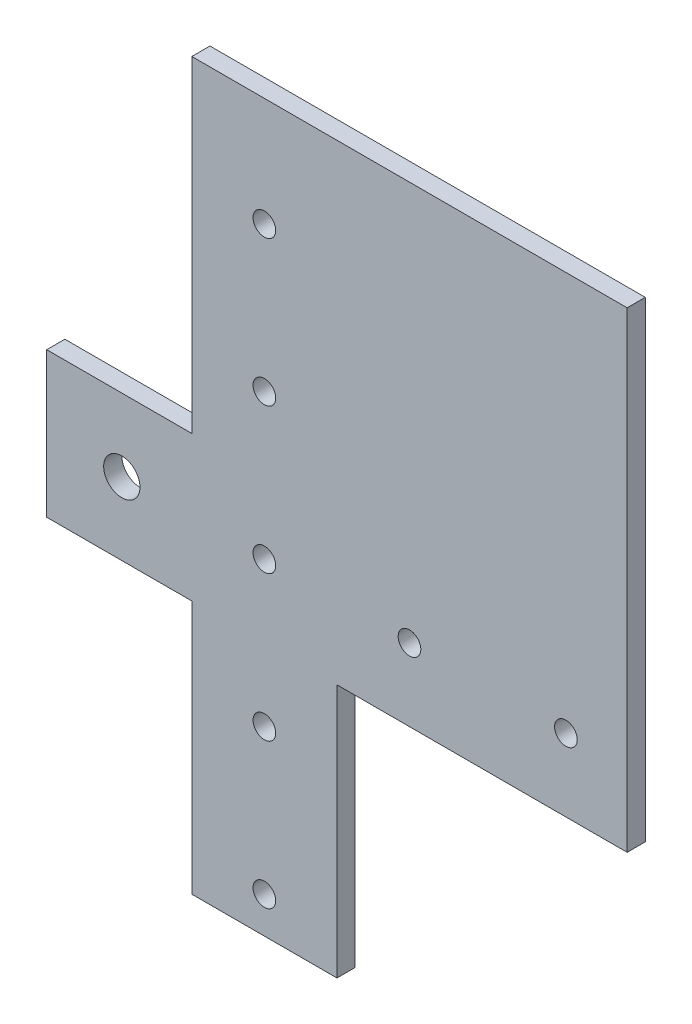
SolidWorks part; units mm, degrees
ref_plane "Front Plane" through (0, 0, 0) normal (0, 0, 1) x (1, 0, 0)
ref_plane "Top Plane" through (0, 0, 0) normal (0, 1, 0) x (1, 0, 0)
ref_plane "Right Plane" through (0, 0, 0) normal (1, 0, 0) x (0, 0, -1)
sketch "Sketch1" plane through (0, 0, 0) normal (0, 0, 1) x (1, 0, 0)
  line L1 (0, -1.7869) -> (101.6, -1.7869)
  line L2 (0, -1.7869) -> (0, 125.2131)
  line L3 (0, 125.2131) -> (101.6, 125.2131)
  line L4 (101.6, -1.7869) -> (101.6, 125.2131)
  line L5 (0, 125.2131) -> (25.4, 125.2131)
  line L6 (0, 125.2131) -> (0, 68.0631)
  line L7 (0, 68.0631) -> (25.4, 68.0631)
  line L8 (25.4, 125.2131) -> (25.4, 68.0631)
  line L9 (0, -1.7869) -> (25.4, -1.7869)
  line L10 (0, -1.7869) -> (0, 42.6631)
  line L11 (0, 42.6631) -> (25.4, 42.6631)
  line L12 (25.4, -1.7869) -> (25.4, 42.6631)
  line L13 (101.6, -1.7869) -> (50.8, -1.7869)
  line L14 (101.6, -1.7869) -> (101.6, 42.6631)
  line L15 (101.6, 42.6631) -> (50.8, 42.6631)
  line L16 (50.8, -1.7869) -> (50.8, 42.6631)
  circle A0 centre (38.1, 106.1631) radius 1.9844
  circle A1 centre (38.1, 80.7631) radius 1.9844
  circle A2 centre (38.1, 55.3631) radius 1.9844
  circle A3 centre (38.1, 29.9631) radius 1.9844
  circle A4 centre (38.1, 4.5631) radius 1.9844
  circle A6 centre (63.5, 55.3631) radius 1.9844
  circle A7 centre (90.8844, 55.3631) radius 1.9844
  circle A8 centre (13.1436, 55.3631) radius 3.175
  dimension "D7" = 3.9688
  dimension "D8" = 57.15
  dimension "D9" = 12.7
  dimension "D10" = 25.4
  dimension "D11" = 25.4
  dimension "D12" = 25.4
  dimension "D13" = 25.4
  dimension "D14" = 25.4
  dimension "D15" = 25.4
  dimension "D16" = 6.35
  dimension "D1" = 101.6
  dimension "D2" = 127
  dimension "D3" = 44.45
  dimension "D4" = 69.85
  dimension "D5" = 25.4
  dimension "D6" = 25.4
  dimension "D17" = 25.4
extrude "Boss-Extrude1" add sketch "Sketch1" along normal blind 3.175 contours L12 L1 L4 L3 L8 L7 L2 L11 A8 A7 A6 A4 A3 A2 A1 A0
